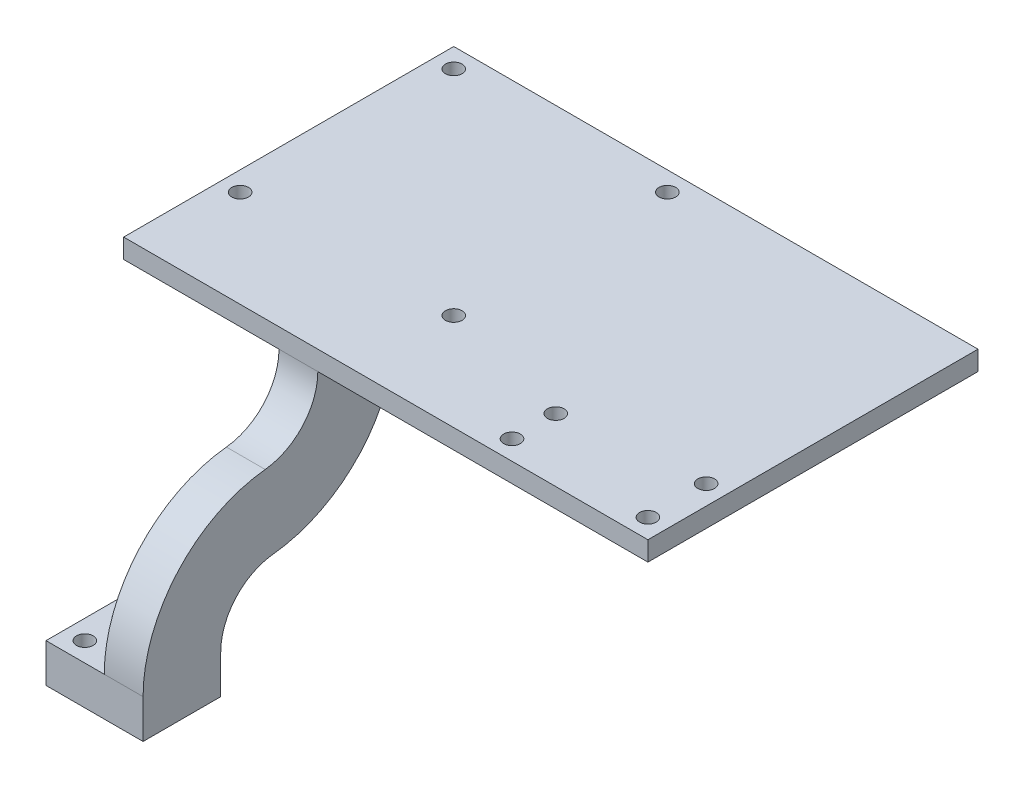
SolidWorks part; units mm, degrees
material "ABS"
ref_plane "Front" through (0, 0, 0) normal (0, 0, 1) x (1, 0, 0)
ref_plane "Top" through (0, 0, 0) normal (0, 1, 0) x (1, 0, 0)
ref_plane "Right" through (0, 0, 0) normal (1, 0, 0) x (0, 0, -1)
sketch "Sketch1" plane through (0, 0, 0) normal (1, 0, 0) x (0, 0, -1)
  line L0 (-10, 0) -> (-10, -10)
  line L1 (0, 0) -> (0, -10) construction
  line L2 (10, 0) -> (-10, 0) construction
  line L3 (55, 50) -> (35, 50)
  line L4 (-10, -10) -> (10, -10)
  line L5 (10, -10) -> (10, 0)
  arc A0 (0, 0) -> (22.5, 25) centre (25.1389, 0) cw construction
  arc A1 (22.5, 25) -> (45, 50) centre (19.8611, 50) ccw construction
  arc A2 (10, 0) -> (23.5497, 15.0552) centre (25.1389, 0) cw
  arc A3 (23.5497, 15.0552) -> (55, 50) centre (19.8611, 50) ccw
  arc A4 (-10, 0) -> (21.4503, 34.9448) centre (25.1389, 0) cw
  arc A5 (21.4503, 34.9448) -> (35, 50) centre (19.8611, 50) ccw
  point P0 (0, -11.4389)
  dimension "D3" = 45
  dimension "D4" = 50
  dimension "D5" = 10
  dimension "D1" = 10
  dimension "D2" = 10
extrude "Boss-Extrude1" add sketch "Sketch1" along normal blind 10
sketch "Sketch2" plane through (10, 0, 0) normal (1, 0, 0) x (0, 0, -1)
  line L1 (-10, -10) -> (10, -10)
  line L2 (-10, -10) -> (-10, 0)
  line L3 (-10, 0) -> (10, 0)
  line L4 (10, -10) -> (10, 0)
extrude "Boss-Extrude2" add sketch "Sketch2" against normal blind 25
hole_wizard "#6 Clearance Hole1" positions "Sketch3" profile "Sketch4" hole size "#6" standard "ANSI Inch" end condition through all
sketch "Sketch3" plane through (0, 0, 0) normal (0, 1, 0) x (1, 0, 0)
  line L0 (-10, -5) -> (-10, 5) construction
  line L2 (-15, 10) -> (-15, -10) construction
  line L3 (-15, 10) -> (-15, -10) construction
  point P0 (-10, 5)
  point P2 (-10, -5)
  point P10 (-15, 0)
  point P11 (-10, 0)
  dimension "D1" = 10
  dimension "D2" = 5
sketch "Sketch4" plane through (-10, 0, -5) normal (1, 0, 0) x (0, 0, 1)
  line L0 (0, 0) -> (0, 10)
  line L1 (0, 10) -> (2.1526, 10)
  line L2 (2.1526, 10) -> (2.1526, 0)
  line L5 (2.1526, 0) -> (0, 0)
  line L11 (0, -6.35) -> (0, 107.95) construction
  dimension "Thru Hole Dia." = 4.3053
  dimension "Thru Hole Depth" = 10
sketch "Sketch5" plane through (0, 50, 0) normal (0, 1, 0) x (1, 0, 0)
  line L0 (10, 35) -> (0, 35) construction
  line L1 (95, 35) -> (-40, 35)
  line L2 (95, 35) -> (95, 120)
  line L3 (95, 120) -> (-40, 120)
  line L4 (-40, 35) -> (-40, 120)
  line L5 (0, 55) -> (0, 35) construction
  point P5 (0, 35)
  dimension "D1" = 85
  dimension "D2" = 135
  dimension "D3" = 40
extrude "Boss-Extrude3" add sketch "Sketch5" along normal blind 5
hole_wizard "#6 Clearance Hole2" positions "Sketch7" profile "Sketch8" hole size "#6" standard "ANSI Inch" end condition through all
sketch "Sketch7" plane through (0, 55, 0) normal (0, 1, 0) x (1, 0, 0)
  line L0 (-35, 115) -> (-35, 60) construction
  line L1 (-35, 60) -> (20, 60) construction
  line L2 (20, 60) -> (20, 115) construction
  line L3 (20, 115) -> (-35, 115) construction
  line L5 (-40, 120) -> (-40, 35) construction
  line L6 (95, 120) -> (-40, 120) construction
  point P0 (20, 115)
  point P2 (20, 60)
  point P4 (-35, 60)
  point P6 (-35, 115)
  dimension "D1" = 5
  dimension "D2" = 5
  dimension "D3" = 55
  dimension "D4" = 55
sketch "Sketch8" plane through (20, 55, -115) normal (1, 0, 0) x (0, 0, 1)
  line L0 (0, 0) -> (0, 65)
  line L1 (0, 65) -> (2.1526, 65)
  line L2 (2.1526, 65) -> (2.1526, 0)
  line L5 (2.1526, 0) -> (0, 0)
  line L11 (0, -6.35) -> (0, 107.95) construction
  dimension "Thru Hole Dia." = 4.3053
  dimension "Thru Hole Depth" = 65
hole_wizard "#6 Clearance Hole3" positions "Sketch9" profile "Sketch10" hole size "#6" standard "ANSI Inch" end condition through all
sketch "Sketch9" plane through (0, 55, 0) normal (0, 1, 0) x (1, 0, 0)
  line L0 (55, 40) -> (55, 55) construction
  line L1 (55, 55) -> (90, 55) construction
  line L2 (90, 55) -> (90, 40) construction
  line L3 (90, 40) -> (55, 40) construction
  line L5 (-40, 35) -> (95, 35) construction
  line L6 (95, 35) -> (95, 120) construction
  point P0 (90, 40)
  point P2 (55, 40)
  point P4 (55, 51.2661)
  point P6 (90, 55)
  dimension "D1" = 35
  dimension "D2" = 15
  dimension "D3" = 5
  dimension "D4" = 5
sketch "Sketch10" plane through (90, 55, -40) normal (1, 0, 0) x (0, 0, 1)
  line L0 (0, 0) -> (0, 65)
  line L1 (0, 65) -> (2.1526, 65)
  line L2 (2.1526, 65) -> (2.1526, 0)
  line L5 (2.1526, 0) -> (0, 0)
  line L11 (0, -6.35) -> (0, 107.95) construction
  dimension "Thru Hole Dia." = 4.3053
  dimension "Thru Hole Depth" = 65
